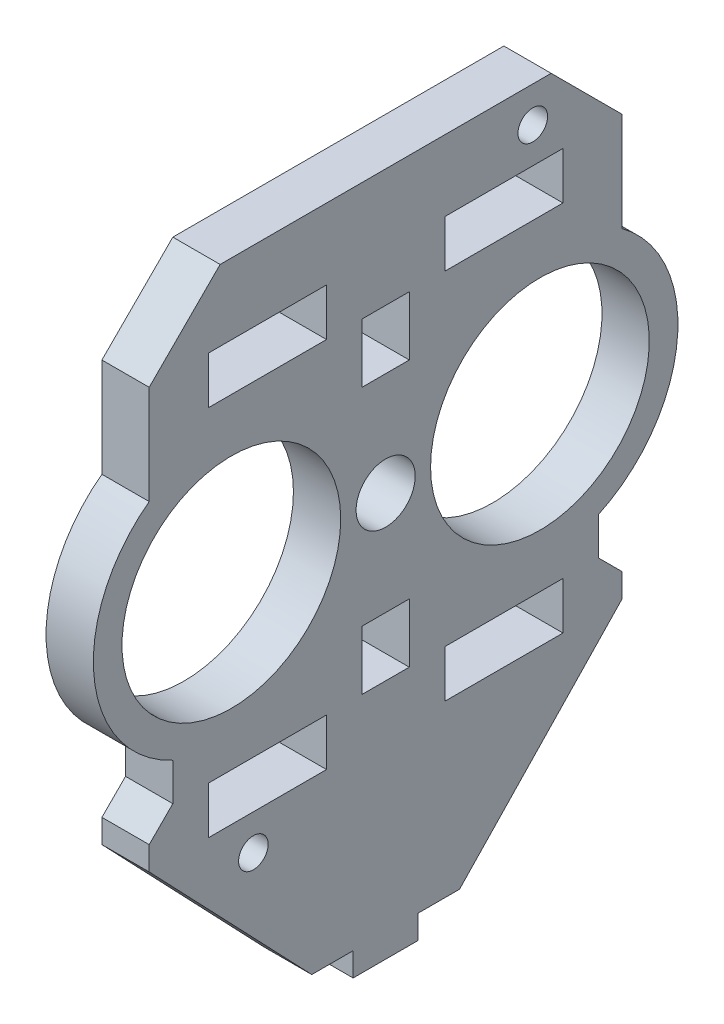
SolidWorks part; units mm, degrees
ref_plane "Front Plane" through (0, 0, 0) normal (0, 0, 1) x (1, 0, 0)
ref_plane "Top Plane" through (0, 0, 0) normal (0, 1, 0) x (1, 0, 0)
ref_plane "Right Plane" through (0, 0, 0) normal (1, 0, 0) x (0, 0, -1)
sketch "Sketch1" plane through (0, 0, 0) normal (1, 0, 0) x (0, 0, -1)
  line L0 (0, 86.3618) -> (0, -95.6447) construction
  line L1 (-34.45, 0) -> (67.35, 0) construction
  line L2 (-12.5, -64.29) -> (-40, -35.5)
  line L3 (-40, -31.5) -> (-40, -35.5)
  line L4 (-40, -31.5) -> (-36, -27.5)
  line L5 (-12.5, -64.29) -> (-12.5, -68.29)
  line L6 (-12.5, -68.29) -> (12.5, -68.29)
  line L7 (12.5, -64.29) -> (12.5, -68.29)
  line L8 (-36, -27.5) -> (-36, -21.1431)
  line L9 (-40, 35.5) -> (-40, 18.7571)
  line L10 (-40, 35.5) -> (-28, 47.5)
  line L11 (40, 35.5) -> (-40, 35.5) construction
  line L12 (40, 35.5) -> (40, 18.7571)
  line L13 (40, -35.5) -> (40, -31.5)
  line L14 (40, -31.5) -> (36, -27.5)
  line L15 (36, -27.5) -> (36, -21.1431)
  line L16 (12.5, -64.29) -> (40, -35.5)
  line L17 (40, -35.5) -> (30, -35.5) construction
  line L18 (40, 35.5) -> (28, 47.5)
  line L19 (-28, 47.5) -> (28, 47.5)
  line L22 (-40, -35.5) -> (-40, -27.5) construction
  line L24 (-30, -27.5) -> (-40, -27.5) construction
  circle A0 centre (0, 0) radius 76.29 construction
  circle A1 centre (-22.3739, -41.5) radius 2.5
  circle A2 centre (24.8916, 41.5) radius 2.5
  circle A3 centre (-26.1, 0) radius 23.3461 construction
  circle A4 centre (-26.1, 0) radius 18.5
  circle A5 centre (26.1, 0) radius 18.5
  circle A6 centre (26.1, 0) radius 23.3461 construction
  circle A7 centre (0, 0) radius 5
  arc A9 (-40, 18.7571) -> (-36, -21.1431) centre (-26.1, 0) ccw
  arc A10 (40, 18.7571) -> (36, -21.1431) centre (26.1, 0) cw
  circle A11 centre (-26.1, 0) radius 8.35 construction
  circle A13 centre (70, 0) radius 2.65 construction
  circle A14 centre (-43.3013, -25) radius 7 construction
  point P14 (0, 0)
  point P16 (0, -76.29)
  point P20 (-62.4774, 0)
  point P27 (0, -68.29)
  point P30 (0, 56.7762)
  point P31 (0, 56.7762)
  dimension "D1" = 152.58
  dimension "D2" = 5
  dimension "D5" = 37
  dimension "D9" = 8
  dimension "D7" = 6
  dimension "D10" = 4
  dimension "D3" = 6
  dimension "D4" = 5
  dimension "D13" = 10
  dimension "D6" = 124.9548
  dimension "D8" = 25
  dimension "D11" = 12
  dimension "D12" = 12
  dimension "D15" = 4
extrude "Boss-Extrude1" add sketch "Sketch1" along normal blind 8
sketch "Sketch2" plane through (0, 0, 0) normal (-1, 0, 0) x (0, 0, 1)
  line L0 (0, -90.2636) -> (0, 91.611) construction
  line L1 (-93.4475, 0) -> (84.8595, 0) construction
  line L2 (10, -27.5) -> (10, -35.5)
  line L3 (-30, -27.5) -> (-10, -27.5)
  line L4 (-30, -27.5) -> (-30, -35.5)
  line L5 (-30, -35.5) -> (-10, -35.5)
  line L6 (-10, -27.5) -> (-10, -35.5)
  line L7 (30, -35.5) -> (10, -35.5)
  line L8 (30, -27.5) -> (30, -35.5)
  line L9 (30, -27.5) -> (10, -27.5)
  line L10 (30, 27.5) -> (10, 27.5)
  line L11 (30, 27.5) -> (30, 35.5)
  line L12 (30, 35.5) -> (10, 35.5)
  line L13 (-10, 27.5) -> (-10, 35.5)
  line L14 (-30, 35.5) -> (-10, 35.5)
  line L15 (-30, 27.5) -> (-30, 35.5)
  line L16 (-30, 27.5) -> (-10, 27.5)
  line L17 (10, 27.5) -> (10, 35.5)
  line L18 (4, 17.5) -> (4, 27.5)
  line L19 (-4, -17.5) -> (4, -17.5)
  line L20 (-4, -17.5) -> (-4, -27.5)
  line L21 (-4, -27.5) -> (4, -27.5)
  line L22 (4, -17.5) -> (4, -27.5)
  line L23 (-4, 27.5) -> (4, 27.5)
  line L24 (-4, 17.5) -> (-4, 27.5)
  line L25 (-4, 17.5) -> (4, 17.5)
  line L26 (5.5, -68.29) -> (5.5, -64.29)
  line L27 (-12.5, -68.29) -> (-5.5, -68.29)
  line L28 (-12.5, -68.29) -> (-12.5, -64.29)
  line L29 (-12.5, -64.29) -> (-5.5, -64.29)
  line L30 (-5.5, -68.29) -> (-5.5, -64.29)
  line L31 (12.5, -64.29) -> (5.5, -64.29)
  line L32 (12.5, -68.29) -> (12.5, -64.29)
  line L33 (12.5, -68.29) -> (5.5, -68.29)
  point P26 (0, -17.5)
  dimension "D1" = 27.5
  dimension "D2" = 20
  dimension "D3" = 20
  dimension "D4" = 8
  dimension "D5" = 8
  dimension "D6" = 10
  dimension "D7" = 4
  dimension "D8" = 7
extrude "Cut-Extrude1" cut sketch "Sketch2" against normal up to next
